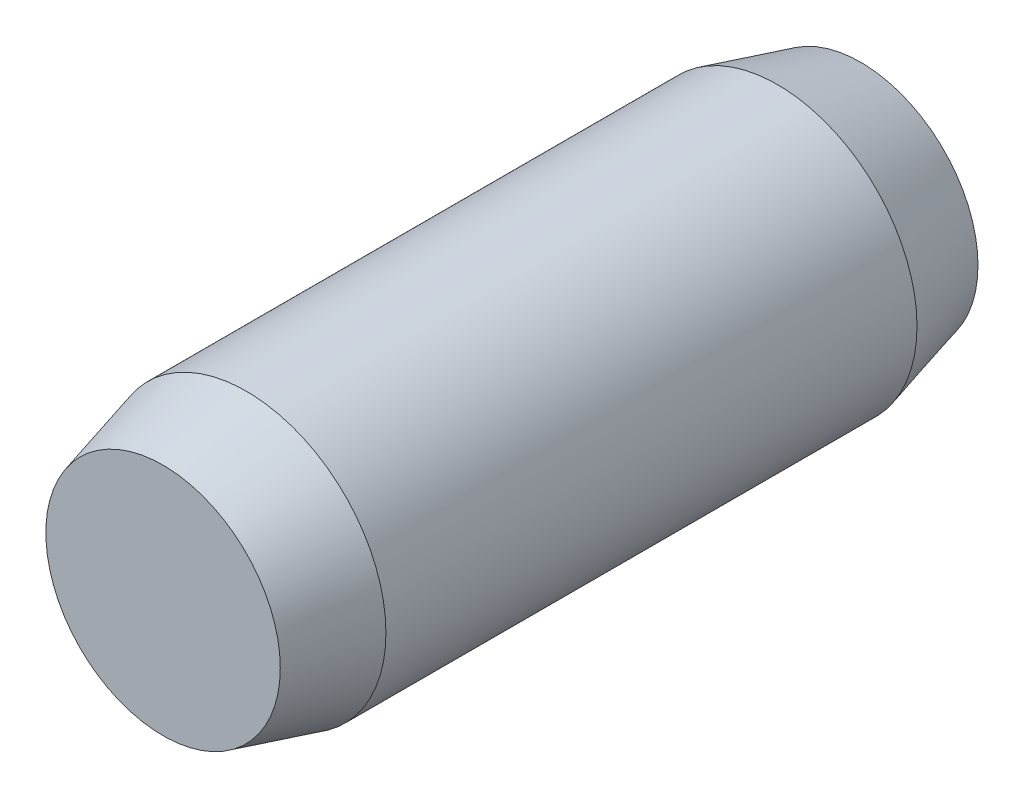
SolidWorks part; units mm, degrees
material "AISI 304"
ref_plane "Front Plane" through (0, 0, 0) normal (0, 0, 1) x (1, 0, 0)
ref_plane "Top Plane" through (0, 0, 0) normal (0, 1, 0) x (1, 0, 0)
ref_plane "Right Plane" through (0, 0, 0) normal (1, 0, 0) x (0, 0, -1)
sketch "Sketch1" plane through (0, 0, 0) normal (1, 0, 0) x (0, 0, -1)
  line L0 (-3.9688, 0) -> (3.9688, 0)
  dimension "Length" = 7.9375
sketch "Sketch2" plane through (0, 0, 0) normal (0, 0, 1) x (1, 0, 0)
  circle A0 centre (0, 0) radius 1.5875
  dimension "Diameter" = 3.175
sketch "Sketch3" plane through (0, 0, 0) normal (1, 0, 0) x (0, 0, -1)
  line L0 (-3.9688, 0) -> (-3.9688, 1.3335)
  line L1 (-3.9688, 1.3335) -> (-3.0208, 1.5875)
  line L2 (-3.0208, 1.5875) -> (3.0208, 1.5875)
  line L5 (3.9688, 0) -> (-3.9688, 0)
  line L6 (-3.9688, 0) -> (3.9688, 0) construction
  line L7 (-3.9688, 0) -> (3.9688, 0) construction
  line L8 (3.0208, 1.5875) -> (3.9688, 1.3335)
  line L9 (3.9688, 1.3335) -> (3.9688, 0)
  point P0 (0, 1.5875)
  dimension "D1" = 15
  dimension "D2" = 1.3335
revolve "Revolve1" add sketch "Sketch3" angle 360 about L0
equation "\"D2@Sketch3\"=\"Diameter@Sketch2\"*.42"
